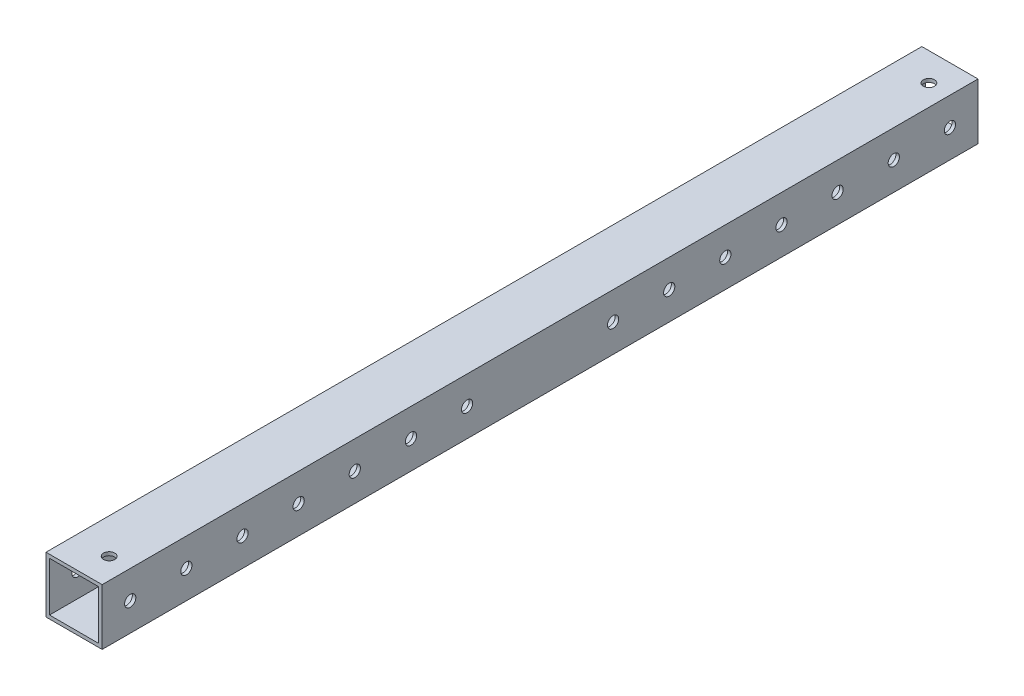
SolidWorks part; units mm, degrees
ref_plane "Front Plane" through (0, 0, 0) normal (0, 0, 1) x (1, 0, 0)
ref_plane "Top Plane" through (0, 0, 0) normal (0, 1, 0) x (1, 0, 0)
ref_plane "Right Plane" through (0, 0, 0) normal (1, 0, 0) x (0, 0, -1)
sketch "Sketch1" plane through (0, 0, 0) normal (0, 0, 1) x (1, 0, 0)
  line L1 (0, 0) -> (25.4, 0)
  line L2 (0, 0) -> (0, 25.4)
  line L3 (0, 25.4) -> (25.4, 25.4)
  line L4 (25.4, 0) -> (25.4, 25.4)
  line L5 (1.5875, 1.5875) -> (23.8125, 1.5875)
  line L6 (1.5875, 1.5875) -> (1.5875, 23.8125)
  line L7 (1.5875, 23.8125) -> (23.8125, 23.8125)
  line L8 (23.8125, 1.5875) -> (23.8125, 23.8125)
  dimension "D1" = 25.4
  dimension "D2" = 1.5875
  dimension "D3" = 1.5875
  dimension "D4" = 1.5875
  dimension "D5" = 1.5875
extrude "Boss-Extrude1" add sketch "Sketch1" along normal blind 396.24
sketch "Sketch3" plane through (0, 25.4, 0) normal (0, 1, 0) x (1, 0, 0)
  line L0 (0, -396.24) -> (0, 0) construction
  line L1 (25.4, -396.24) -> (0, -396.24) construction
  line L2 (25.4, 0) -> (0, 0) construction
  circle A0 centre (15.875, -383.54) radius 2.54
  circle A1 centre (15.875, -12.7) radius 2.54
  dimension "D3" = 5.08
  dimension "D1" = 15.875
  dimension "D2" = 12.7
  dimension "D4" = 12.7
extrude "Cut-Extrude2" cut sketch "Sketch3" against normal through all
sketch "Sketch4" plane through (25.4, 0, 0) normal (1, 0, 0) x (0, 0, -1)
  line L0 (-396.24, 25.4) -> (0, 25.4) construction
  line L1 (-396.24, 0) -> (-396.24, 25.4) construction
  line L3 (-198.12, 25.4) -> (-198.12, 0) construction
  line L4 (-396.24, 0) -> (0, 0) construction
  circle A0 centre (-383.54, 12.7) radius 2.54
  circle A2 centre (-358.14, 12.7) radius 2.54
  circle A3 centre (-332.74, 12.7) radius 2.54
  circle A4 centre (-307.34, 12.7) radius 2.54
  circle A5 centre (-281.94, 12.7) radius 2.54
  circle A11 centre (-256.54, 12.7) radius 2.54
  circle A12 centre (-231.14, 12.7) radius 2.54
  circle A13 centre (-165.1, 12.7) radius 2.54
  circle A14 centre (-139.7, 12.7) radius 2.54
  circle A15 centre (-114.3, 12.7) radius 2.54
  circle A16 centre (-88.9, 12.7) radius 2.54
  circle A17 centre (-63.5, 12.7) radius 2.54
  circle A18 centre (-38.1, 12.7) radius 2.54
  circle A19 centre (-12.7, 12.7) radius 2.54
  dimension "D1" = 5.08
  dimension "D2" = 12.7
  dimension "D3" = 12.7
  dimension "D4" = 7
extrude "Cut-Extrude3" cut sketch "Sketch4" against normal through all
